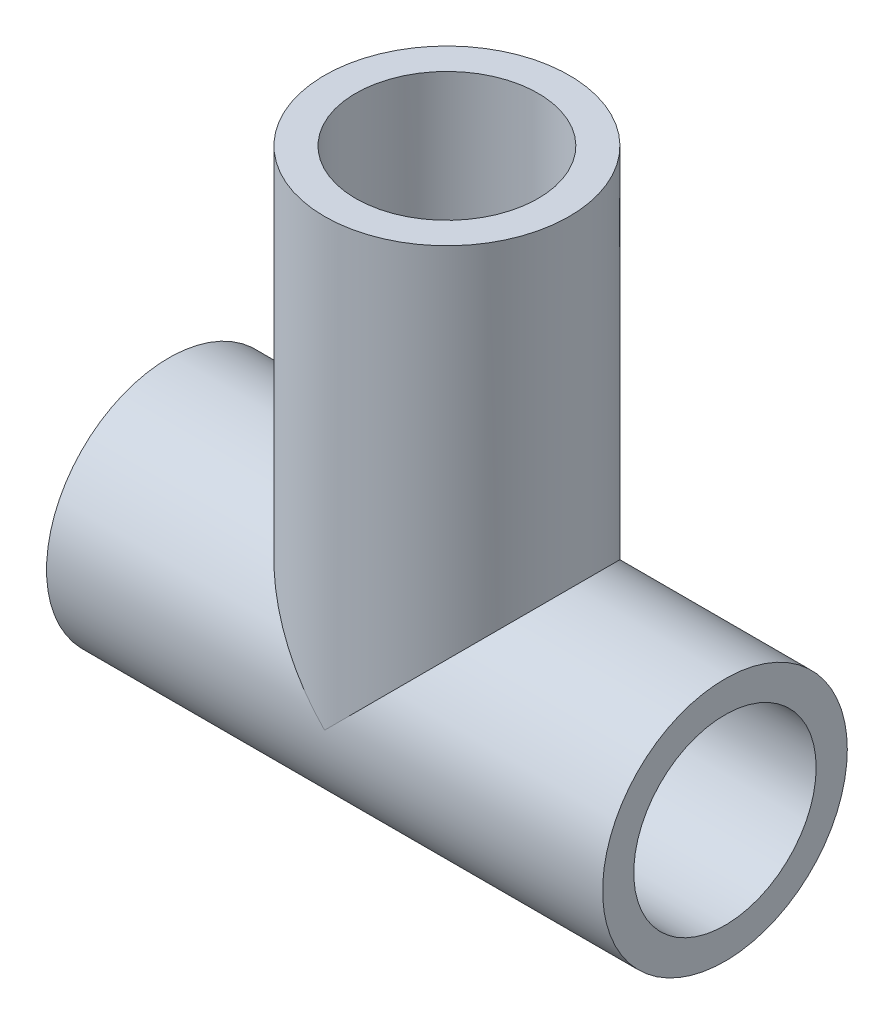
SolidWorks part; units mm, degrees
ref_plane "前视基准面" through (0, 0, 0) normal (0, 0, 1) x (1, 0, 0)
ref_plane "上视基准面" through (0, 0, 0) normal (0, 1, 0) x (1, 0, 0)
ref_plane "右视基准面" through (0, 0, 0) normal (1, 0, 0) x (0, 0, -1)
other "Configuration Table"
sketch "草图1" plane through (0, 0, 0) normal (1, 0, 0) x (0, 0, -1)
  circle A0 centre (0, 0) radius 4.1
  circle A1 centre (0, 0) radius 5.5
  dimension "D1" = 8.2
  dimension "D2" = 11
extrude "凸台-拉伸1" add sketch "草图1" along normal mid plane 25
sketch "草图3" plane through (0, 0, 0) normal (0, 1, 0) x (1, 0, 0)
  circle A0 centre (0, 0) radius 5.5
extrude "凸台-拉伸2" add sketch "草图3" along normal blind 20
sketch "草图4" plane through (0, 0, 0) normal (1, 0, 0) x (0, 0, -1)
  circle A0 centre (0, 0) radius 4.1
extrude "切除-拉伸2" cut sketch "草图4" against normal mid plane 45
sketch "草图5" plane through (0, 0, 0) normal (0, 1, 0) x (1, 0, 0)
  circle A0 centre (0, 0) radius 4.1
  dimension "D1" = 8.2
extrude "切除-拉伸3" cut sketch "草图5" along normal blind 45
